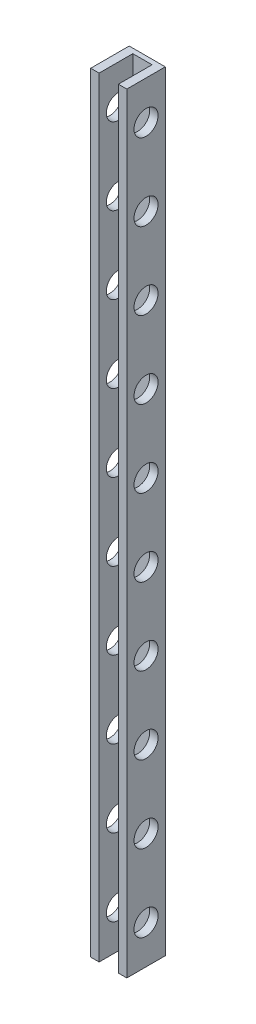
SolidWorks part; units mm, degrees
ref_plane "Plan de face" through (0, 0, 0) normal (0, 0, 1) x (1, 0, 0)
ref_plane "Plan de dessus" through (0, 0, 0) normal (0, 1, 0) x (1, 0, 0)
ref_plane "Plan de droite" through (0, 0, 0) normal (1, 0, 0) x (0, 0, -1)
sketch "Esquisse1" plane through (0, 0, 0) normal (0, 1, 0) x (1, 0, 0)
  line L0 (-2, -4) -> (-2, 3)
  line L1 (3.75, 4) -> (-3.75, 4)
  line L2 (3.75, 4) -> (3.75, -4)
  line L3 (3.75, -4) -> (2, -4)
  line L4 (-3.75, 4) -> (-3.75, -4)
  line L5 (3.75, 4) -> (-3.75, -4) construction
  line L6 (3.75, -4) -> (-3.75, 4) construction
  line L7 (-2, 3) -> (2, 3)
  line L8 (2, 3) -> (2, -4)
  line L9 (-2, 3) -> (2, -4) construction
  line L10 (0, -1.2247) -> (0, 2.1498) construction
  line L11 (-2, -4) -> (-3.75, -4)
  point P0 (0, 0)
  point P8 (0, -0.5)
  dimension "D1" = 7.5
  dimension "D2" = 8
  dimension "D3" = 1
  dimension "D4" = 4
extrude "Base" add sketch "Esquisse1" against normal blind 160
sketch "Esquisse2" plane through (-3.75, 0, 0) normal (-1, 0, 0) x (0, 0, 1)
  line L0 (0, 0) -> (0, -160) construction
  line L1 (-4, -160) -> (4, -160) construction
  line L3 (0, -5.5) -> (3.0778, -5.5) construction
  line L4 (-4, 0) -> (4, 0) construction
  circle A0 centre (0, -8) radius 2.5
  circle A1 centre (0, -24) radius 2.5
  circle A2 centre (0, -40) radius 2.5
  circle A3 centre (0, -56) radius 2.5
  circle A4 centre (0, -72) radius 2.5
  circle A5 centre (0, -88) radius 2.5
  circle A6 centre (0, -104) radius 2.5
  circle A7 centre (0, -120) radius 2.5
  circle A8 centre (0, -136) radius 2.5
  circle A9 centre (0, -152) radius 2.5
  dimension "D1" = 5
  dimension "D2" = 5.5
  dimension "D3" = 10
extrude "Trou" cut sketch "Esquisse2" against normal through all
